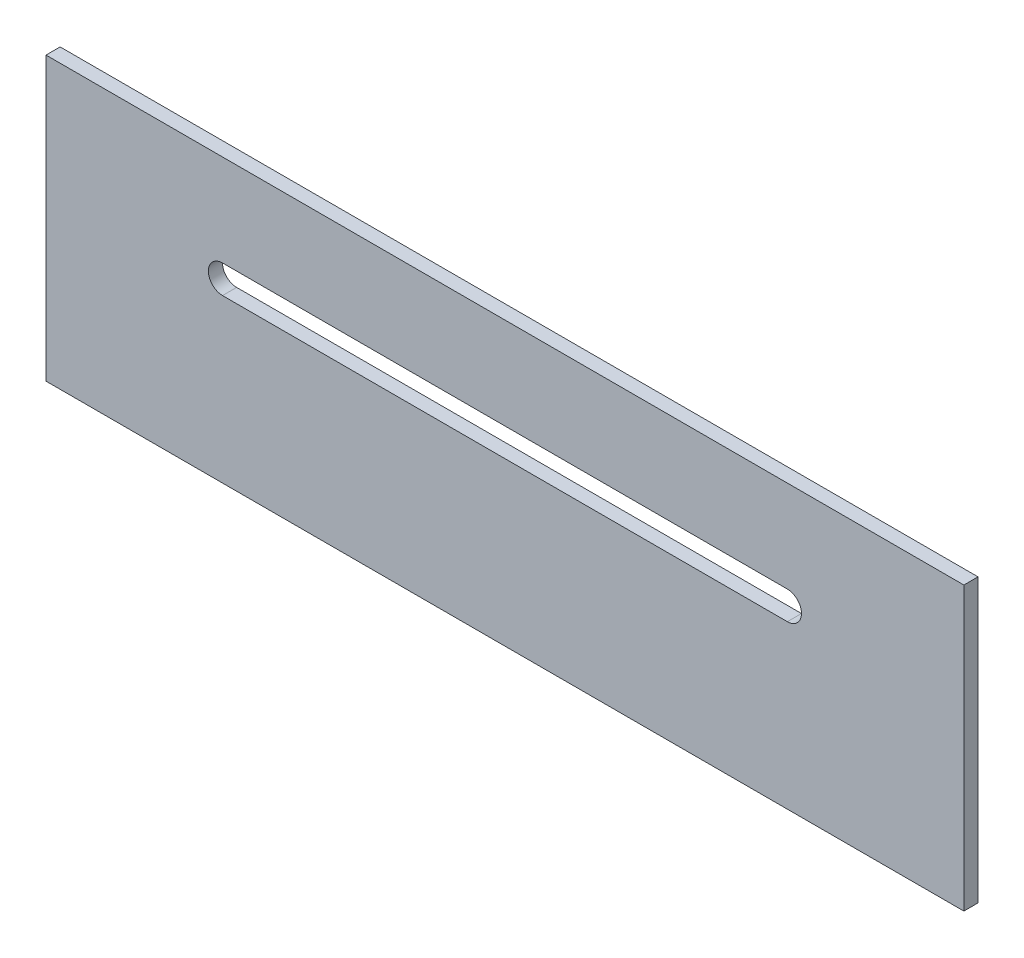
SolidWorks part; units mm, degrees
ref_plane "Front Plane" through (0, 0, 0) normal (0, 0, 1) x (1, 0, 0)
ref_plane "Top Plane" through (0, 0, 0) normal (0, 1, 0) x (1, 0, 0)
ref_plane "Right Plane" through (0, 0, 0) normal (1, 0, 0) x (0, 0, -1)
sketch "Sketch1" plane through (0, 0, 0) normal (0, 0, 1) x (1, 0, 0)
  line L1 (-65, 20) -> (65, 20)
  line L2 (-65, 20) -> (-65, -20)
  line L3 (-65, -20) -> (65, -20)
  line L4 (65, 20) -> (65, -20)
  line L5 (-65, 20) -> (65, -20) construction
  line L6 (-65, -20) -> (65, 20) construction
  point P0 (0, 0)
  dimension "D1" = 130
  dimension "D2" = 40
extrude "Boss-Extrude1" add sketch "Sketch1" along normal blind 2
sketch "Sketch2" plane through (0, 0, 2) normal (0, 0, 1) x (1, 0, 0)
  line L0 (-40, 5) -> (40, 5) construction
  line L1 (-40, 7) -> (40, 7)
  line L2 (-40, 3) -> (40, 3)
  line L3 (-65, -20) -> (65, -20) construction
  line L6 (-65, 20) -> (-65, -20) construction
  arc A0 (-40, 7) -> (-40, 3) centre (-40, 5) ccw
  arc A1 (40, 3) -> (40, 7) centre (40, 5) ccw
  point P2 (0, 5)
  dimension "D1" = 2
  dimension "D4" = 25
  dimension "D2" = 25
  dimension "D3" = 80
extrude "Cut-Extrude1" cut sketch "Sketch2" against normal through all
